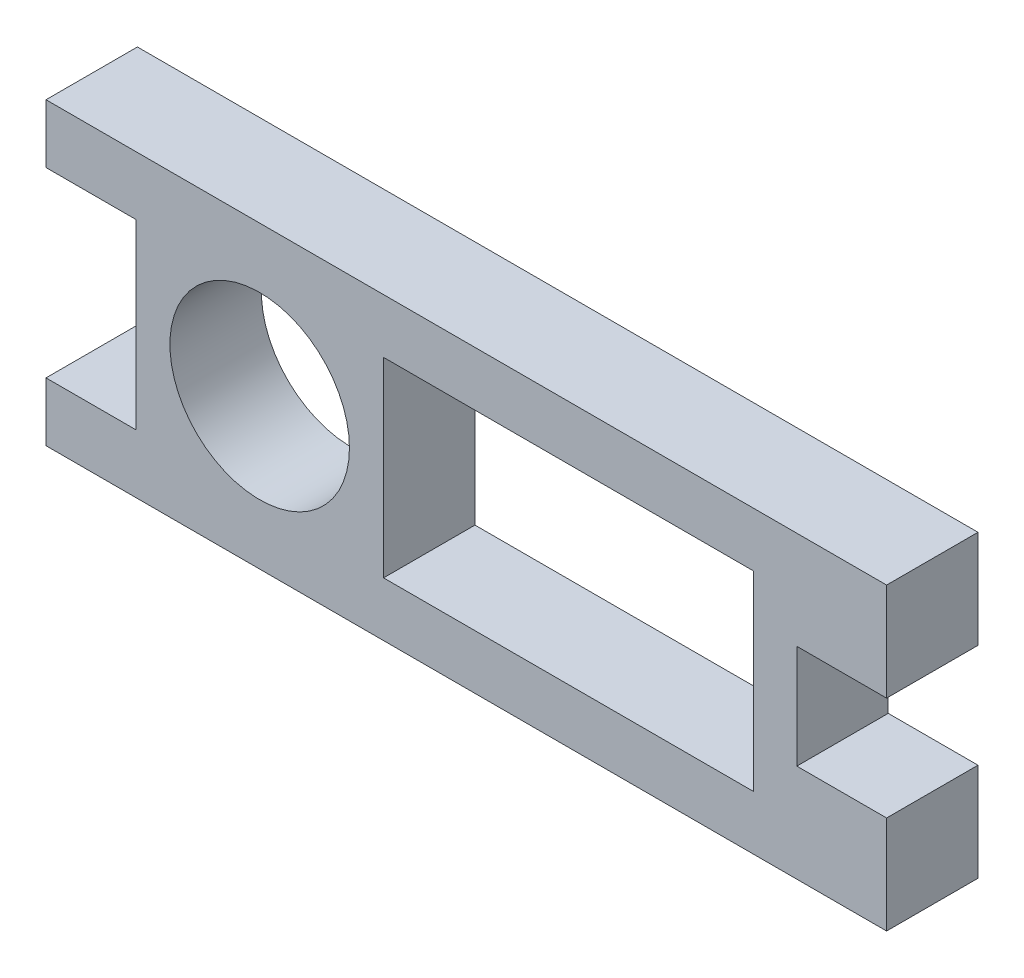
SolidWorks part; units mm, degrees
material "Acrylic (Medium-high impact)"
ref_plane "Front Plane" through (0, 0, 0) normal (0, 0, 1) x (1, 0, 0)
ref_plane "Top Plane" through (0, 0, 0) normal (0, 1, 0) x (1, 0, 0)
ref_plane "Right Plane" through (0, 0, 0) normal (1, 0, 0) x (0, 0, -1)
sketch "Sketch1" plane through (0, 0, 0) normal (0, 0, 1) x (1, 0, 0)
  line L0 (-297.7097, 397.165) -> (49702.2903, 397.165) construction
  line L1 (702.2903, 402.744) -> (702.2903, 391.586)
  line L2 (702.2903, 402.744) -> (696.7903, 402.744)
  line L3 (696.7903, 402.744) -> (696.7903, 406.344)
  line L4 (696.7903, 406.344) -> (748.2903, 406.344)
  line L5 (748.2903, 406.344) -> (748.2903, 400.344)
  line L6 (748.2903, 400.344) -> (742.7903, 400.344)
  line L7 (742.7903, 400.344) -> (742.7903, 393.986)
  line L8 (742.7903, 393.986) -> (748.2903, 393.986)
  line L9 (748.2903, 393.986) -> (748.2903, 387.986)
  line L10 (748.2903, 387.986) -> (696.7903, 387.986)
  line L11 (696.7903, 387.986) -> (696.7903, 391.586)
  line L12 (696.7903, 391.586) -> (702.2903, 391.586)
  line L13 (709.8808, -602.835) -> (709.8808, 49397.165) construction
  line L14 (717.4713, 391.315) -> (740.1403, 391.315)
  line L15 (717.4713, 391.315) -> (717.4713, 403.015)
  line L16 (717.4713, 403.015) -> (740.1403, 403.015)
  line L17 (740.1403, 391.315) -> (740.1403, 403.015)
  circle A0 centre (709.8808, 397.165) radius 5.5
  point P0 (702.2903, 397.165)
  point P19 (717.4713, 397.165)
  dimension "D10" = 11
  dimension "D1" = 11.158
  dimension "D2" = 3.6
  dimension "D3" = 40.5
  dimension "D4" = 5.5
  dimension "D5" = 5.5
  dimension "D6" = 6
  dimension "D7" = 22.669
  dimension "D8" = 2.65
  dimension "D9" = 11.7
extrude "Boss-Extrude1" add sketch "Sketch1" along normal blind 5.6
